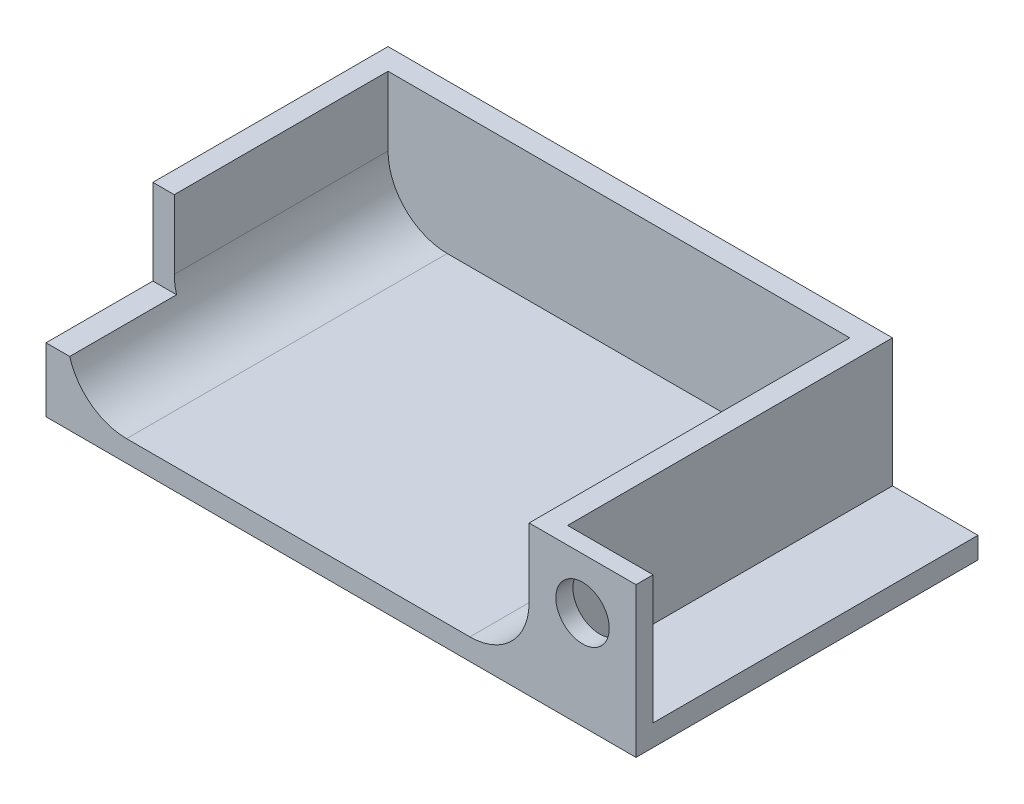
SolidWorks part; units mm, degrees
ref_plane "Plan de face" through (0, 0, 0) normal (0, 0, 1) x (1, 0, 0)
ref_plane "Plan de dessus" through (0, 0, 0) normal (0, 1, 0) x (1, 0, 0)
ref_plane "Plan de droite" through (0, 0, 0) normal (1, 0, 0) x (0, 0, -1)
sketch "Esquisse1" plane through (0, 0, 0) normal (0, 1, 0) x (1, 0, 0)
  line L1 (0, 0) -> (138, 0)
  line L2 (0, 0) -> (0, 75)
  line L3 (0, 75) -> (138, 75)
  line L4 (138, 0) -> (138, 75)
  dimension "D1" = 138
  dimension "D2" = 75
extrude "Boss.-Extru.1" add sketch "Esquisse1" along normal blind 5
sketch "Esquisse2" plane through (0, 5, 0) normal (0, 1, 0) x (1, 0, 0)
  line L0 (0, 0) -> (138, 0) construction
  line L1 (0, 75) -> (5, 75)
  line L2 (0, 75) -> (0, 0)
  line L3 (0, 0) -> (5, 0)
  line L4 (5, 75) -> (5, 0)
  line L6 (138, 75) -> (113, 75)
  line L7 (138, 75) -> (138, 0)
  line L8 (138, 0) -> (113, 0)
  line L9 (113, 75) -> (113, 0)
  dimension "D1" = 25
  dimension "D2" = 5
extrude "Boss.-Extru.2" add sketch "Esquisse2" along normal blind 30
fillet "Congé1" radius 13.85 2 edges at (113, 5, -37.5) (5, 5, -37.5)
sketch "Esquisse3" plane through (0, 0, -75) normal (0, 0, -1) x (-1, 0, 0)
  line L1 (-138, 0) -> (0, 0)
  line L2 (-138, 0) -> (-138, 35)
  line L3 (-138, 35) -> (0, 35)
  line L4 (0, 0) -> (0, 35)
extrude "Boss.-Extru.3" add sketch "Esquisse3" along normal blind 5
sketch "Esquisse4" plane through (0, 0, 0) normal (-1, 0, 0) x (0, 0, 1)
  line L1 (0, 35) -> (-25, 35)
  line L2 (0, 35) -> (0, 15)
  line L3 (0, 15) -> (-25, 15)
  line L4 (-25, 35) -> (-25, 15)
  dimension "D1" = 25
  dimension "D2" = 20
extrude "Enlèv. mat.-Extru.1" cut sketch "Esquisse4" against normal blind 6
sketch "Esquisse5" plane through (0, 35, 0) normal (0, 1, 0) x (1, 0, 0)
  line L0 (113, 75) -> (113, 0) construction
  line L1 (138, 80) -> (118, 80)
  line L2 (138, 80) -> (138, 4)
  line L3 (138, 4) -> (118, 4)
  line L4 (118, 80) -> (118, 4)
  line L5 (113, 0) -> (138, 0) construction
  dimension "D1" = 5
  dimension "D2" = 4
extrude "Enlèv. mat.-Extru.2" cut sketch "Esquisse5" against normal blind 30
sketch "Esquisse6" plane through (0, 0, 0) normal (0, 0, 1) x (1, 0, 0)
  line L0 (113, 35) -> (138, 35) construction
  line L3 (138, 35) -> (138, 0) construction
  circle A0 centre (125.5, 23) radius 6.25
  point P6 (138, 25.8437)
  dimension "D3" = 12.5
  dimension "D1" = 12
  dimension "D2" = 12.5
extrude "Enlèv. mat.-Extru.3" cut sketch "Esquisse6" against normal up to surface (4 mm away) up to face at (128, 20, -4)
